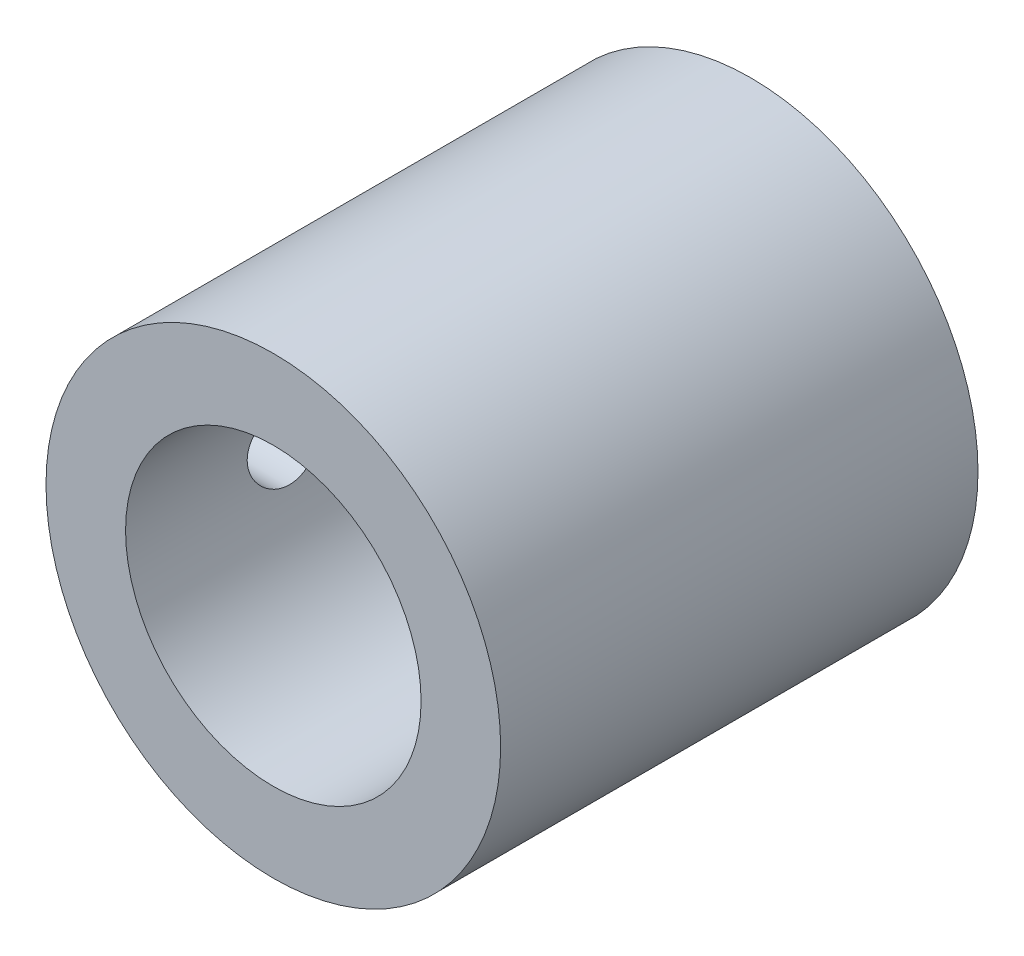
SolidWorks part; units mm, degrees
material "3.1355 (EN-AW 2024)"
ref_plane "Front" through (0, 0, 0) normal (0, 0, 1) x (1, 0, 0)
ref_plane "Top" through (0, 0, 0) normal (0, 1, 0) x (1, 0, 0)
ref_plane "Right" through (0, 0, 0) normal (1, 0, 0) x (0, 0, -1)
sketch "Эскиз1" plane through (0, 0, 0) normal (0, 0, 1) x (1, 0, 0)
  circle A0 centre (0, 0) radius 10
  dimension "D1" = 20
extrude "Бобышка-Вытянуть1" add sketch "Эскиз1" along normal blind 21
sketch "Эскиз2" plane through (0, 0, 21) normal (0, 0, 1) x (1, 0, 0)
  circle A0 centre (0, 0) radius 6.5
  dimension "D1" = 13
extrude "Вырез-Вытянуть1" cut sketch "Эскиз2" against normal blind 15
sketch "Эскиз3" plane through (0, 0, 0) normal (0, 1, 0) x (1, 0, 0)
  line L0 (-10, -21) -> (-10, -16) construction
  dimension "D1" = 5
ref_plane "Плоскость1" through (-10, 0, 0) normal (1, 0, 0) x (0, 0, -1)
hole_wizard "Отверстие обработанное метчиком M4x0.71" positions "Эскиз5" profile "Эскиз4" tap size "M4x0.7" standard "Ansi Metric"
sketch "Эскиз5" plane through (-10, 0, 0) normal (1, 0, 0) x (0, 0, -1)
  line L0 (-21, 0) -> (-16, 0) construction
  point P0 (-14, 0)
sketch "Эскиз4" plane through (-10, 0, 14) normal (0, 1, 0) x (0, 0, 1)
  line L0 (0, 0) -> (0, 5.9914)
  line L1 (0, 5.9914) -> (1.65, 5)
  line L2 (1.65, 5) -> (1.65, 0)
  line L5 (1.65, 0) -> (0, 0)
  line L10 (0, 5.9914) -> (-1.65, 5) construction
  line L11 (0, -6.35) -> (0, 107.95) construction
  dimension "Диаметр сверла" = 3.3
  dimension "Глубина сверла" = 5
  dimension "Угол заточки сверла" = 118
cosmetic thread "Отверстие резьбы1" parameters "D1"=3.7129, "D2"=4
sketch "Эскиз7" plane through (0, 0, 0) normal (0, 0, -1) x (-1, 0, 0)
  line L0 (-6, 0) -> (0, 0) construction
  line L1 (0, 0) -> (-4.2426, 4.2426) construction
  line L2 (0, 0) -> (4.2426, 4.2426) construction
  line L3 (0, 0) -> (4.2426, -4.2426) construction
  line L4 (0, 0) -> (-4.2426, -4.2426) construction
  circle A0 centre (0, 0) radius 6 construction
  point P11 (0, 0)
  dimension "D1" = 12
  dimension "D2" = 45
  dimension "D3" = 4
hole_wizard "Отверстие обработанное метчиком M3x0.51" positions "Эскиз9" profile "Эскиз8" tap size "M3x0.5" standard "Ansi Metric"
sketch "Эскиз9" plane through (0, 0, 0) normal (0, 0, -1) x (-1, 0, 0)
  point P0 (-4.2426, 4.2426)
  point P3 (4.2426, 4.2426)
  point P6 (4.2426, -4.2426)
  point P9 (-4.2426, -4.2426)
sketch "Эскиз8" plane through (4.2426, 4.2426, 0) normal (1, 0, 0) x (0, 1, 0)
  line L0 (0, 0) -> (0, 6)
  line L1 (0, 6) -> (1.25, 6)
  line L2 (1.25, 6) -> (1.25, 0)
  line L5 (1.25, 0) -> (0, 0)
  line L11 (0, -6.35) -> (0, 107.95) construction
  dimension "Диаметр проходного сверла" = 2.5
  dimension "Глубина проходного сверла" = 6
cosmetic thread "Отверстие резьбы2" parameters "D2"=3
cosmetic thread "Отверстие резьбы3" parameters "D2"=3
cosmetic thread "Отверстие резьбы4" parameters "D2"=3
cosmetic thread "Отверстие резьбы5" parameters "D2"=3
